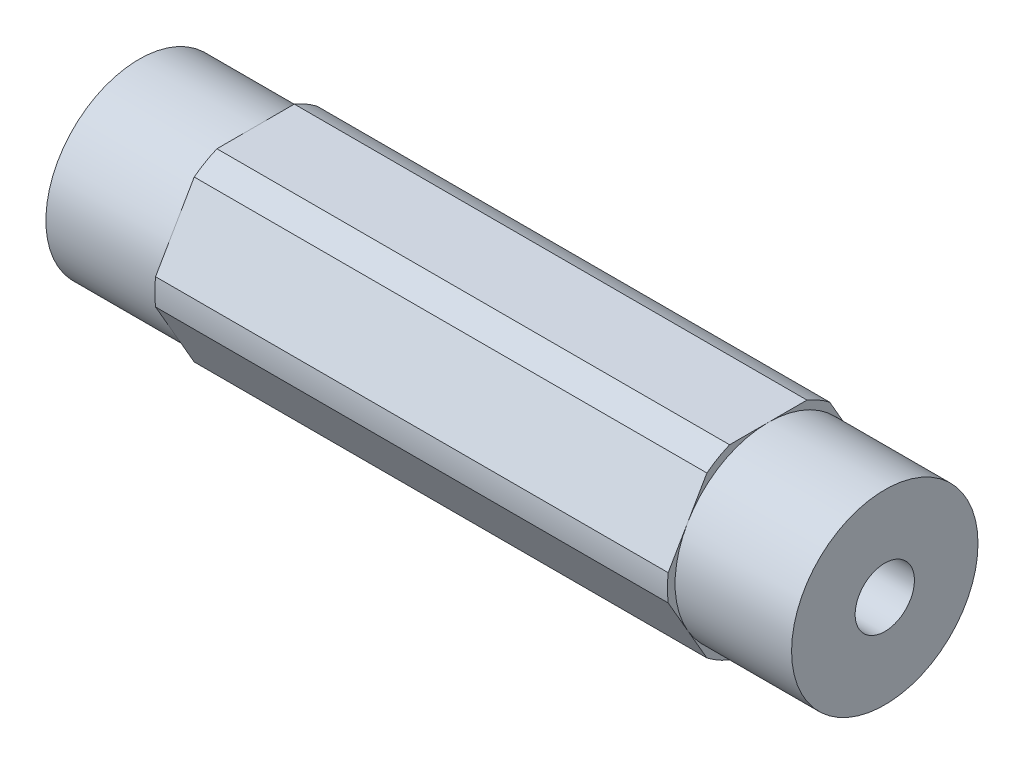
SolidWorks part; units mm, degrees
material "7075-T6 (SN)"
ref_plane "Front Plane" through (0, 0, 0) normal (0, 0, 1) x (1, 0, 0)
ref_plane "Top Plane" through (0, 0, 0) normal (0, 1, 0) x (1, 0, 0)
ref_plane "Right Plane" through (0, 0, 0) normal (1, 0, 0) x (0, 0, -1)
sketch "Sketch1" plane through (0, 0, 0) normal (1, 0, 0) x (0, 0, -1)
  line L1 (3.6662, 6.35) -> (-3.6662, 6.35)
  line L2 (-3.6662, 6.35) -> (-7.3323, 0)
  line L3 (-7.3323, 0) -> (-3.6662, -6.35)
  line L4 (-3.6662, -6.35) -> (3.6662, -6.35)
  line L5 (3.6662, -6.35) -> (7.3323, 0)
  line L6 (7.3323, 0) -> (3.6662, 6.35)
  circle A0 centre (0, 0) radius 6.875
  circle A1 centre (0, 0) radius 2.0193
  circle A2 centre (0, 0) radius 6.35 construction
  dimension "D1" = 12.7
  dimension "D2" = 13.75
  dimension "D3" = 4.0386
extrude "Boss-Extrude1" add sketch "Sketch1" along normal mid plane 50.8 contours L6 A0 L1 L2 L3 L4 L5 A1
sketch "Sketch3" plane through (25.4, 0, 0) normal (1, 0, 0) x (0, 0, -1)
  circle A0 centre (0, 0) radius 6.35
  dimension "D1" = 12.7
extrude "Cut-Extrude-Thin1" cut sketch "Sketch3" against normal blind 7.9375 thin
mirror "Mirror1" about plane through (0, 0, 0) normal (1, 0, 0) of "Cut-Extrude-Thin1"
equation "\"D2@Sketch1\"=13.75mm"
